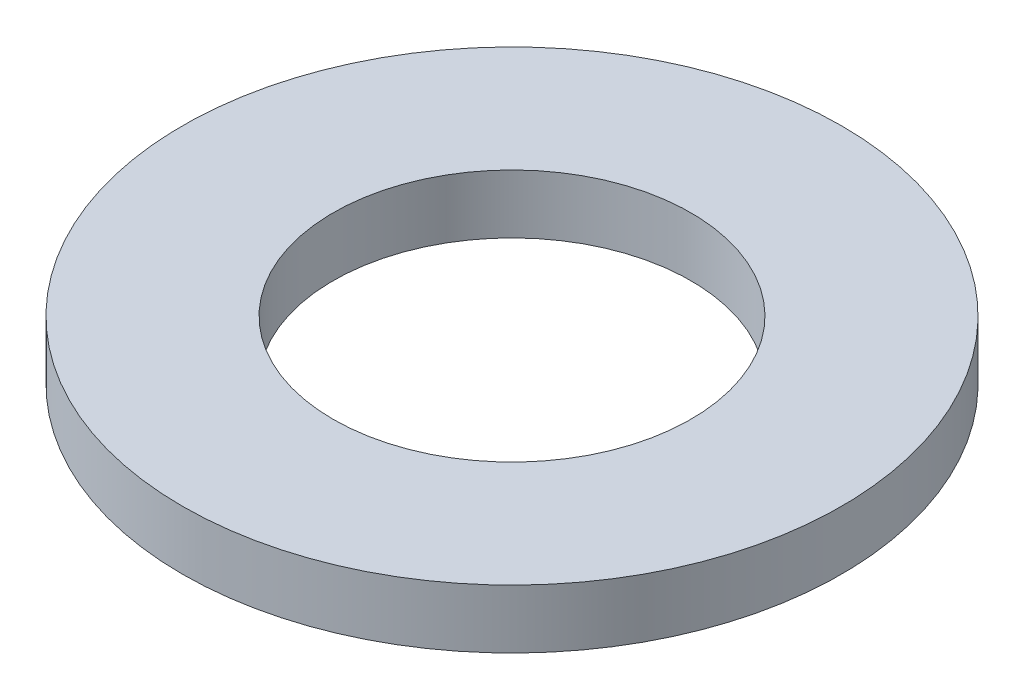
SolidWorks part; units mm, degrees
material "Plain Carbon Steel"
ref_plane "Front Plane" through (0, 0, 0) normal (0, 0, 1) x (1, 0, 0)
ref_plane "Top Plane" through (0, 0, 0) normal (0, 1, 0) x (1, 0, 0)
ref_plane "Right Plane" through (0, 0, 0) normal (1, 0, 0) x (0, 0, -1)
sketch "Sketch1" plane through (0, 0, 0) normal (0, 1, 0) x (1, 0, 0)
  circle A0 centre (0, 0) radius 9.652
  circle A1 centre (0, 0) radius 17.78
  dimension "D1" = 19.304
  dimension "D2" = 35.56
extrude "Boss-Extrude1" add sketch "Sketch1" along normal blind 3.175
